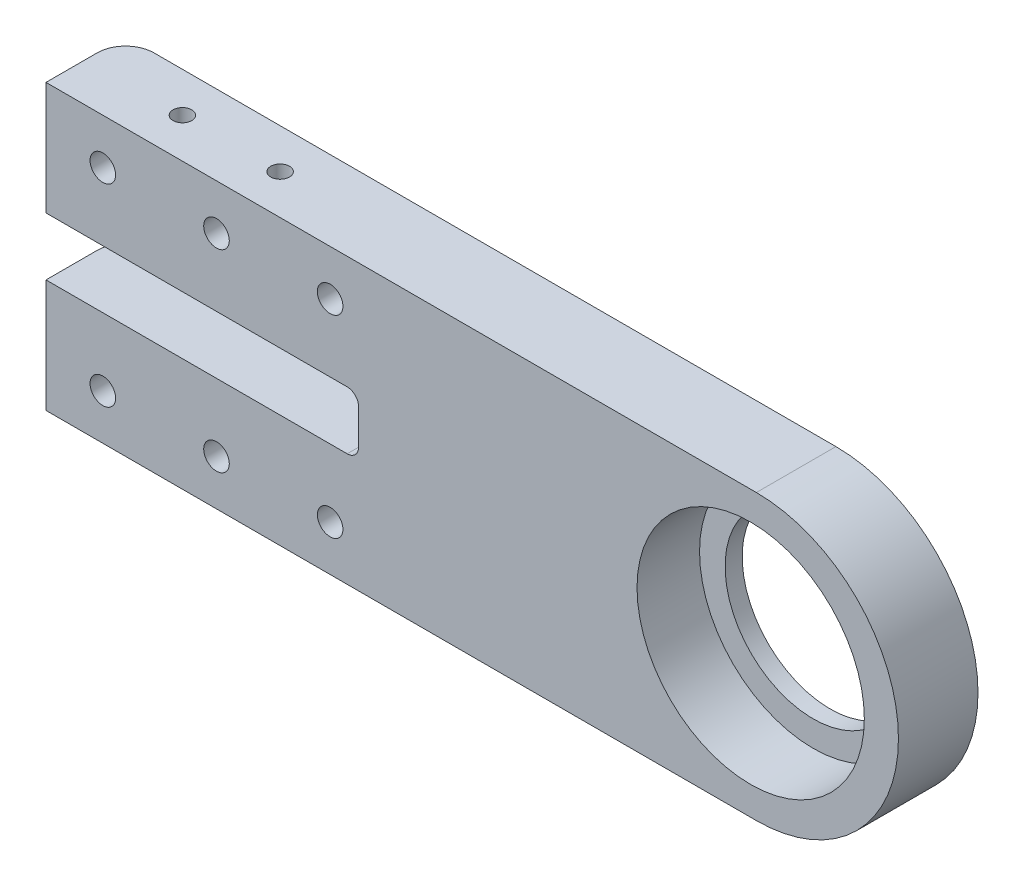
SolidWorks part; units mm, degrees
material "6061 Alloy"
ref_plane "Front" through (0, 0, 0) normal (0, 0, 1) x (1, 0, 0)
ref_plane "Top" through (0, 0, 0) normal (0, 1, 0) x (1, 0, 0)
ref_plane "Right" through (0, 0, 0) normal (1, 0, 0) x (0, 0, -1)
ref_plane "Plane1" through (0, 0, 0) normal (0, 0, -1) x (-1, 0, 0)
sketch "Sketch1" plane through (0, 0, 0) normal (0, 0, -1) x (-1, 0, 0)
  line L0 (0, 0) -> (-125, 0)
  line L1 (-125, -50) -> (0, -50)
  line L2 (0, -50) -> (0, 0)
  arc A0 (-125, 0) -> (-125, -50) centre (-125, -25) ccw
extrude "Boss-Extrude1" add sketch "Sketch1" against normal blind 14
sketch "Sketch2" plane through (0, 0, 14) normal (0, 0, 1) x (1, 0, 0)
  line L0 (0, -19.9) -> (0, -30.1)
  line L1 (0, -30.1) -> (55, -30.1)
  line L2 (55, -30.1) -> (55, -19.9)
  line L3 (55, -19.9) -> (0, -19.9)
extrude "Cut-Extrude1" cut sketch "Sketch2" against normal through all
hole_wizard "CSK for M4 Flat Head Machine Screw1" positions "Sketch4" profile "Sketch3" countersink size "M4" standard "ANSI Metric" end condition through all
sketch "Sketch4" plane through (0, 0, 0) normal (0, 0, -1) x (-1, 0, 0)
  point P0 (-10, -8)
  point P1 (-10, -42)
  point P2 (-30, -42)
  point P3 (-30, -8)
  point P4 (-50, -8)
  point P5 (-50, -42)
sketch "Sketch3" plane through (10, -8, 0) normal (1, 0, 0) x (0, 1, 0)
  line L0 (0, 0) -> (0, 14)
  line L1 (0, 14) -> (2.25, 14)
  line L2 (2.25, 14) -> (2.25, 2.45)
  line L3 (2.25, 2.45) -> (4.7, 0)
  line L5 (4.7, 0) -> (0, 0)
  line L6 (-2.25, 2.45) -> (-4.7, 0) construction
  line L11 (0, -6.35) -> (0, 107.95) construction
  dimension "Thru Hole Dia." = 4.5
  dimension "Thru Hole Depth" = 14
  dimension "Near C'Sink Dia." = 9.4
  dimension "Near C'Sink Angle" = 90
hole_wizard "M4x0.7 Tapped Hole1" positions "Sketch6" profile "Sketch5" tap size "M4x0.7" standard "ANSI Metric"
sketch "Sketch6" plane through (0, 0, 0) normal (0, 1, 0) x (1, 0, 0)
  point P0 (17, -7)
  point P1 (34.2, -7)
sketch "Sketch5" plane through (17, 0, 7) normal (1, 0, 0) x (0, 0, 1)
  line L0 (0, 0) -> (0, 19.9)
  line L1 (0, 19.9) -> (1.65, 19.9)
  line L2 (1.65, 19.9) -> (1.65, 0)
  line L5 (1.65, 0) -> (0, 0)
  line L11 (0, -6.35) -> (0, 107.95) construction
  dimension "Thru Tap Drill Dia." = 3.3
  dimension "Thru Tap Drill Depth" = 19.9
hole_wizard "Hole1" positions "Sketch8" profile "Sketch7" legacy
sketch "Sketch8" plane through (0, 0, 14) normal (0, 0, 1) x (1, 0, 0)
  point P0 (124, -25)
sketch "Sketch7" plane through (124, -25, 14) normal (1, 0, 0) x (0, -1, 0)
  line L0 (0, 0) -> (0, 14)
  line L1 (0, 14) -> (15.5, 14)
  line L2 (15.5, 14) -> (15.5, 11)
  line L3 (15.5, 11) -> (20, 11)
  line L4 (20, 11) -> (20, 0)
  line L5 (20, 0) -> (0, 0)
  line L6 (0, 110) -> (0, -10) construction
  dimension "Diameter" = 31
  dimension "Depth" = 14
  dimension "C-Bore Diameter" = 40
  dimension "C-Bore Depth" = 11
fillet "Fillet1" radius 2 2 edges at (55, -19.9, 7) (55, -30.1, 7)
fillet "Fillet2" radius 5 2 edges at (0, -40.05, 0) (0, -9.95, 0)
